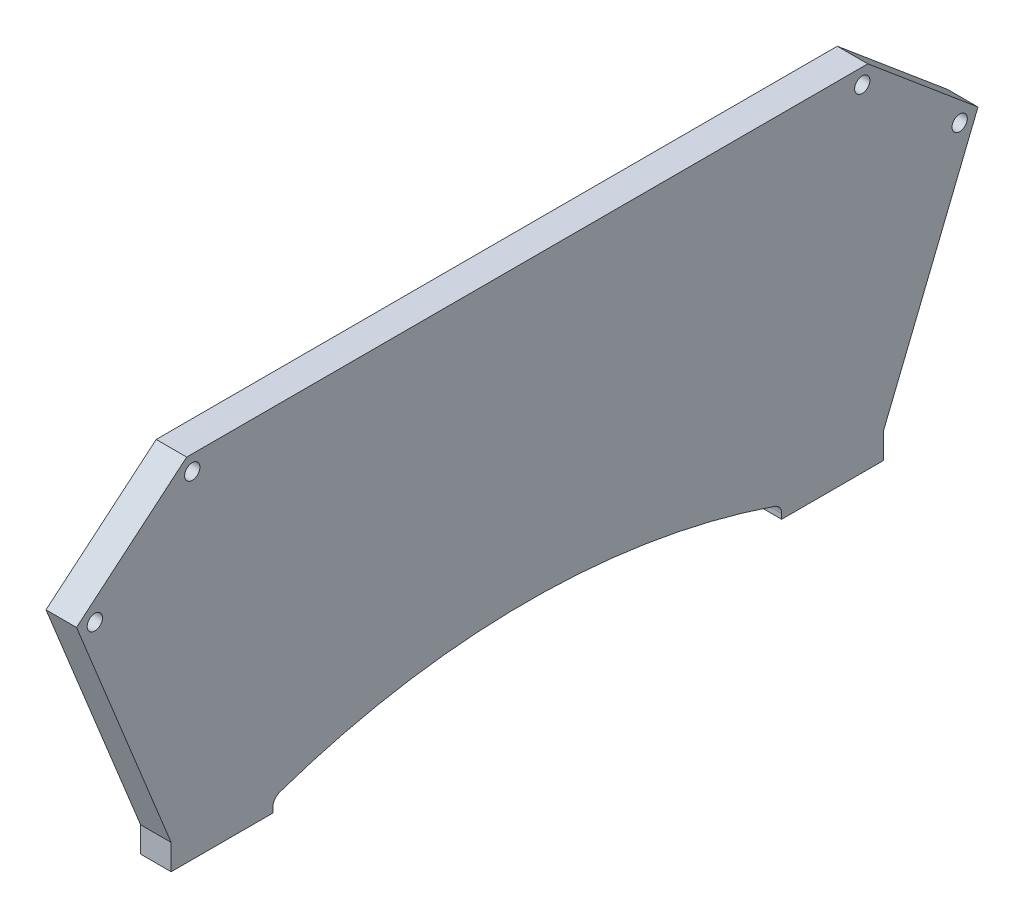
SolidWorks part; units mm, degrees
material "1060 Alloy"
ref_plane "Front Plane" through (0, 0, 0) normal (0, 0, 1) x (1, 0, 0)
ref_plane "Top Plane" through (0, 0, 0) normal (0, 1, 0) x (1, 0, 0)
ref_plane "Right Plane" through (0, 0, 0) normal (1, 0, 0) x (0, 0, -1)
sketch "Sketch1" plane through (0, 0, 0) normal (1, 0, 0) x (0, 0, -1)
  line L0 (0, 0) -> (0, 5)
  line L1 (-60.4789, 57.5279) -> (-34.1246, 26.1201) construction
  line L2 (-60.4789, 57.5279) -> (0.8047, 108.9509) construction
  line L3 (-34.1246, 26.1201) -> (27.1589, 77.5431) construction
  line L4 (-57.0184, 56.5154) -> (-36.4492, 32.0019) construction
  line L5 (0.8047, 108.9509) -> (27.1589, 77.5431) construction
  line L6 (20, 1) -> (20, 0)
  line L7 (0, 0) -> (20, 0)
  line L8 (-36.4492, 32.0019) -> (-13.4679, 51.2856) construction
  line L9 (-34.0371, 75.799) -> (-57.0184, 56.5154) construction
  line L10 (0, 5) -> (-18.5999, 50.8955)
  line L11 (-18.5999, 50.8955) -> (3.0592, 69.0697)
  line L12 (3.0592, 69.0697) -> (136.9408, 69.0697)
  line L13 (136.9408, 69.0697) -> (158.5999, 50.8955)
  line L14 (200.4789, 57.5279) -> (174.1246, 26.1201) construction
  line L15 (200.4789, 57.5279) -> (139.1953, 108.9509) construction
  line L16 (174.1246, 26.1201) -> (112.8411, 77.5431) construction
  line L17 (139.1953, 108.9509) -> (112.8411, 77.5431) construction
  line L18 (176.4492, 32.0019) -> (197.0184, 56.5154) construction
  line L19 (197.0184, 56.5154) -> (174.0371, 75.799) construction
  line L20 (153.4679, 51.2856) -> (176.4492, 32.0019) construction
  line L21 (186.7338, 44.2587) -> (126.9824, 94.3961) construction
  line L22 (-46.7338, 44.2587) -> (13.0176, 94.3961) construction
  line L23 (158.5999, 50.8955) -> (140, 5)
  line L28 (140, 0) -> (140, 5)
  line L43 (140, 0) -> (120, 0)
  line L56 (120, 1) -> (120, 0)
  line L63 (174.6584, 98) -> (-14.1241, 98) construction
  circle A0 centre (-15, 50) radius 1.5
  circle A1 centre (155, 50) radius 1.5
  circle A2 centre (4.1511, 66.0697) radius 1.5
  circle A3 centre (135.8489, 66.0697) radius 1.5
  circle A4 centre (155, 50) radius 3 construction
  circle A5 centre (135.8489, 66.0697) radius 3 construction
  circle A6 centre (-15, 50) radius 3 construction
  circle A7 centre (4.1511, 66.0697) radius 3 construction
  arc A12 (-13.4679, 51.2856) -> (11.6098, 87.6055) centre (-66.9654, 115.0414) ccw construction
  arc A13 (11.6098, 87.6055) -> (6.0858, 94.1888) centre (6.8893, 89.2538) ccw construction
  arc A14 (6.0858, 94.1888) -> (-34.0371, 75.799) centre (19.4603, 12.0432) ccw construction
  arc A15 (174.0371, 75.799) -> (133.9142, 94.1888) centre (120.5397, 12.0432) ccw construction
  arc A16 (133.9142, 94.1888) -> (128.3902, 87.6055) centre (133.1107, 89.2538) ccw construction
  arc A17 (128.3902, 87.6055) -> (153.4679, 51.2856) centre (206.9654, 115.0414) ccw construction
  arc A26 (20, 1) -> (21.3514, 2.8919) centre (22, 1) cw
  arc A44 (120, 1) -> (118.6486, 2.8919) centre (118, 1) ccw
  arc A45 (118.6486, 2.8919) -> (21.3514, 2.8919) centre (70, -139) ccw
  dimension "D1" = 3
  dimension "D8" = 5
  dimension "D11" = 50
  dimension "D12" = 15
  dimension "D14" = 25
  dimension "D16" = 2
  dimension "D17" = 6
  dimension "D21" = 40
  dimension "D22" = 35
  dimension "D23" = 80
  dimension "D24" = 3
  dimension "D18" = 6
  dimension "D29" = 50
  dimension "D25" = 5
  dimension "D28" = 6
  dimension "D39" = 8
  dimension "D56" = 2
  dimension "D57" = 150
  dimension "D4" = 25
  dimension "D6" = 28
  dimension "D7" = 15
  dimension "D9" = 20
  dimension "D10" = 100
  dimension "D13" = 1
  dimension "D15" = 40
  dimension "D19" = 30
  dimension "D20" = 30
  dimension "D26" = 3
  dimension "D27" = 2
  dimension "D32" = 98
extrude "Boss-Extrude1" add sketch "Sketch1" along normal blind 6
hole_wizard "Tap Drill for M3 Tap1" positions "Sketch3" profile "Sketch2" hole size "M3" standard "ISO"
sketch "Sketch3" plane through (0, 0, 0) normal (0, -1, 0) x (-1, 0, 0)
  line L0 (-6, 20) -> (0, 20) construction
  line L1 (0, 0) -> (0, 20) construction
  line L2 (-6, 120) -> (0, 120) construction
  point P0 (-3, 10)
  point P2 (-3, 130)
  dimension "D1" = 10
  dimension "D2" = 3
  dimension "D3" = 10
sketch "Sketch2" plane through (3, 0, -10) normal (1, 0, 0) x (0, 0, -1)
  line L0 (0, 0) -> (0, 10.7511)
  line L1 (0, 10.7511) -> (1.25, 10)
  line L2 (1.25, 10) -> (1.25, 0)
  line L5 (1.25, 0) -> (0, 0)
  line L10 (0, 10.7511) -> (-1.25, 10) construction
  line L11 (0, -6.35) -> (0, 107.95) construction
  dimension "Hole Dia." = 2.5
  dimension "Hole Depth" = 10
  dimension "Drill Angle" = 118
equation "\"ˇ35\"=76.24"
